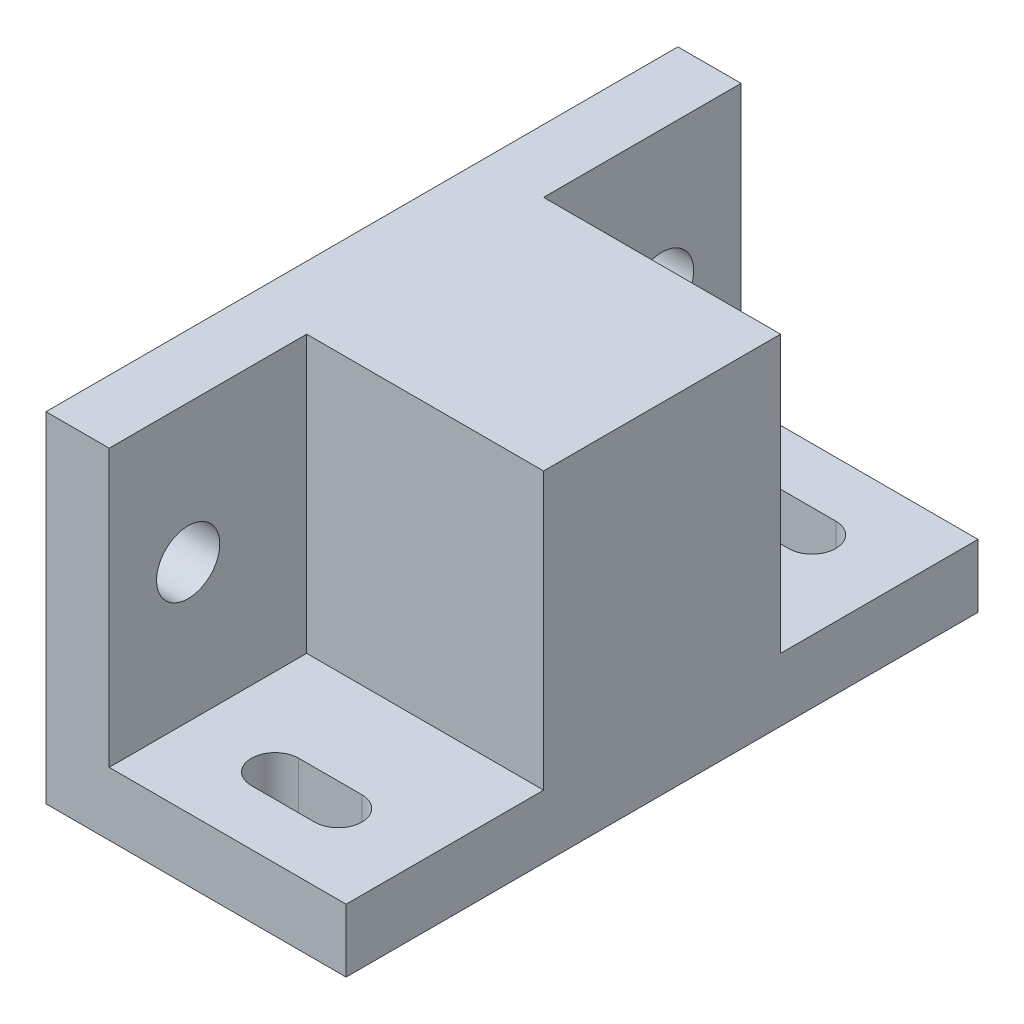
SolidWorks part; units mm, degrees
material "POM 乙缩醛共聚物"
ref_plane "前视基准面" through (0, 0, 0) normal (0, 0, 1) x (1, 0, 0)
ref_plane "上视基准面" through (0, 0, 0) normal (0, 1, 0) x (1, 0, 0)
ref_plane "右视基准面" through (0, 0, 0) normal (1, 0, 0) x (0, 0, -1)
sketch "草图1" plane through (0, 0, 0) normal (0, 0, 1) x (1, 0, 0)
  line L0 (0, 0) -> (15, 0)
  line L1 (15, 0) -> (15, -4)
  line L2 (15, -4) -> (-4, -4)
  line L3 (-4, -4) -> (-4, 17.5)
  line L4 (-4, 17.5) -> (0, 17.5)
  line L5 (0, 17.5) -> (0, 0)
  dimension "D1" = 4
  dimension "D2" = 4
  dimension "D3" = 21.5
  dimension "D4" = 19
extrude "凸台-拉伸1" add sketch "草图1" along normal blind 40
sketch "草图2" plane through (0, 0, 0) normal (0, 1, 0) x (1, 0, 0)
  line L0 (7.5, 0) -> (7.5, -40) construction
  line L1 (15, 0) -> (0, 0) construction
  line L2 (15, -40) -> (0, -40) construction
  line L3 (9.5, -35) -> (5.5, -35) construction
  line L5 (9.5, -36.5) -> (5.5, -36.5)
  line L6 (9.5, -33.5) -> (5.5, -33.5)
  line L7 (15, -20) -> (0, -20) construction
  line L8 (15, -40) -> (15, 0) construction
  line L9 (0, -40) -> (0, 0) construction
  line L10 (9.5, -5) -> (5.5, -5) construction
  line L11 (9.5, -3.5) -> (5.5, -3.5)
  line L12 (9.5, -6.5) -> (5.5, -6.5)
  arc A2 (9.5, -36.5) -> (9.5, -33.5) centre (9.5, -35) ccw
  arc A3 (5.5, -33.5) -> (5.5, -36.5) centre (5.5, -35) ccw
  arc A4 (9.5, -3.5) -> (9.5, -6.5) centre (9.5, -5) cw
  arc A5 (5.5, -6.5) -> (5.5, -3.5) centre (5.5, -5) cw
  point P8 (7.5, -35)
  point P22 (7.5, -5)
  dimension "D1" = 1.5
  dimension "D2" = 15
  dimension "D3" = 4
extrude "切除-拉伸1" cut sketch "草图2" against normal through all
sketch "草图4" plane through (0, 0, 0) normal (1, 0, 0) x (0, 0, -1)
  line L0 (-40, 8.75) -> (0, 8.75) construction
  line L1 (-40, 0) -> (-40, 17.5) construction
  line L2 (0, 0) -> (0, 17.5) construction
  line L3 (-20, 17.5) -> (-20, 0) construction
  line L4 (-40, 17.5) -> (0, 17.5) construction
  line L5 (-40, 0) -> (0, 0) construction
  circle A0 centre (-35, 8.75) radius 2
  circle A1 centre (-5, 8.75) radius 2
  dimension "D1" = 15
  dimension "D2" = 4
extrude "切除-拉伸2" cut sketch "草图4" against normal through all
sketch "草图5" plane through (0, 0, 0) normal (0, 1, 0) x (1, 0, 0)
  line L6 (15, -20) -> (0, -20) construction
  line L7 (15, -40) -> (15, 0) construction
  line L8 (0, -40) -> (0, 0) construction
  line L10 (0, -27.5) -> (15, -27.5)
  line L11 (0, -27.5) -> (0, -12.5)
  line L12 (0, -12.5) -> (15, -12.5)
  line L13 (15, -27.5) -> (15, -12.5)
  point P10 (15, -20)
  dimension "D1" = 15
extrude "凸台-拉伸2" add sketch "草图5" along normal up to surface (17.5 mm away) up to face at (-2, 17.5, 20)
